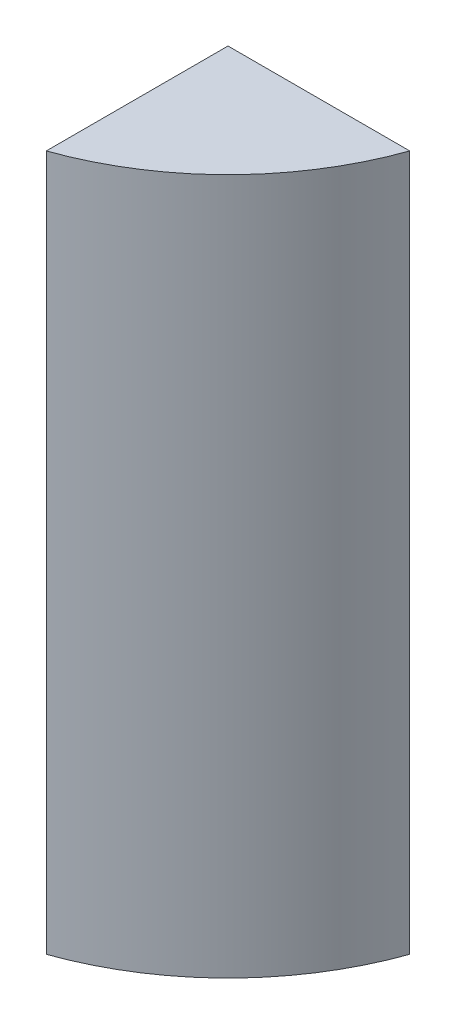
SolidWorks part; units mm, degrees
ref_plane "前视基准面" through (0, 0, 0) normal (0, 0, 1) x (1, 0, 0)
ref_plane "上视基准面" through (0, 0, 0) normal (0, 1, 0) x (1, 0, 0)
ref_plane "右视基准面" through (0, 0, 0) normal (1, 0, 0) x (0, 0, -1)
sketch "草图1" plane through (0, 0, 0) normal (0, 1, 0) x (1, 0, 0)
  line L0 (-56.5685, -20) -> (56.5685, -20)
  line L1 (-56.5685, 20) -> (56.5685, 20)
  line L2 (-20, 56.5685) -> (-20, -56.5685)
  line L3 (20, 56.5685) -> (20, -56.5685)
  circle A0 centre (0, 0) radius 60
  dimension "D1" = 120
  dimension "D2" = 20
  dimension "D3" = 20
  dimension "D4" = 20
  dimension "D5" = 20
extrude "凸台-拉伸1" add sketch "草图1" along normal blind 140 contours L3 A0 L0
